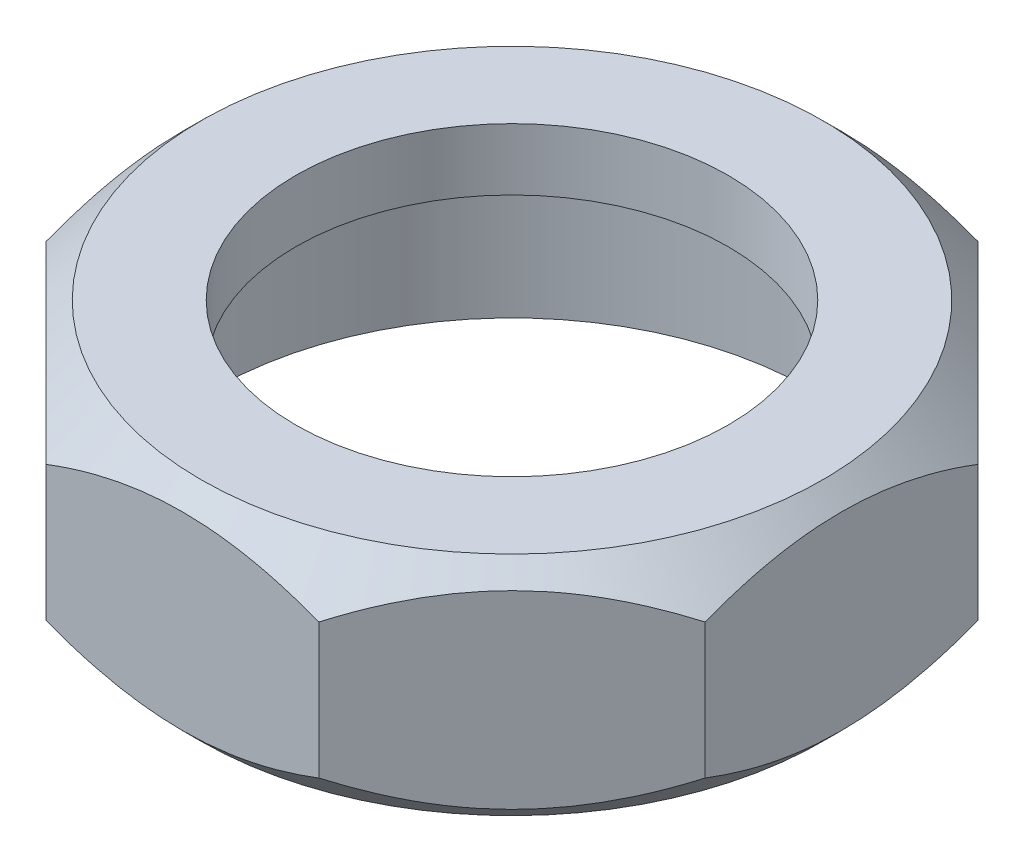
SolidWorks part; units mm, degrees
ref_plane "Front Plane" through (0, 0, 0) normal (0, 0, 1) x (1, 0, 0)
ref_plane "Top Plane" through (0, 0, 0) normal (0, 1, 0) x (1, 0, 0)
ref_plane "Right Plane" through (0, 0, 0) normal (1, 0, 0) x (0, 0, -1)
sketch "Sketch1" plane through (0, 0, 0) normal (0, 1, 0) x (1, 0, 0)
  line L1 (6.6274, 16) -> (-6.6274, 16)
  line L2 (-6.6274, 16) -> (-16, 6.6274)
  line L3 (-16, 6.6274) -> (-16, -6.6274)
  line L4 (-16, -6.6274) -> (-6.6274, -16)
  line L5 (-6.6274, -16) -> (6.6274, -16)
  line L6 (6.6274, -16) -> (16, -6.6274)
  line L7 (16, -6.6274) -> (16, 6.6274)
  line L8 (16, 6.6274) -> (6.6274, 16)
  circle A0 centre (0, 0) radius 10.5
  circle A1 centre (0, 0) radius 16 construction
  dimension "D1" = 21
  dimension "D2" = 32
extrude "Boss-Extrude1" add sketch "Sketch1" along normal mid plane 11
sketch "Sketch2" plane through (0, 0, 0) normal (0, 0, 1) x (1, 0, 0)
  line L0 (0, 0) -> (0, 10.1577) construction
  line L1 (0, 0) -> (-24.9391, 0) construction
  line L2 (-18.5, 2.1) -> (-18.5, 7.5)
  line L3 (-18.5, 7.5) -> (-13.1, 7.5)
  line L4 (-13.1, 7.5) -> (-18.5, 2.1)
  line L5 (-13.1, -7.5) -> (-18.5, -2.1)
  line L6 (-18.5, -7.5) -> (-13.1, -7.5)
  line L7 (-18.5, -2.1) -> (-18.5, -7.5)
  dimension "D1" = 5.4
  dimension "D2" = 18.5
  dimension "D3" = 7.5
  dimension "D4" = 5.4
revolve "Cut-Revolve1" cut sketch "Sketch2" angle 360 about L0
sketch "Sketch3" plane through (0, -5.5, 0) normal (0, -1, 0) x (1, 0, 0)
  circle A0 centre (0, 0) radius 14.5
  dimension "D1" = 29
extrude "Cut-Extrude1" cut sketch "Sketch3" against normal blind 8
